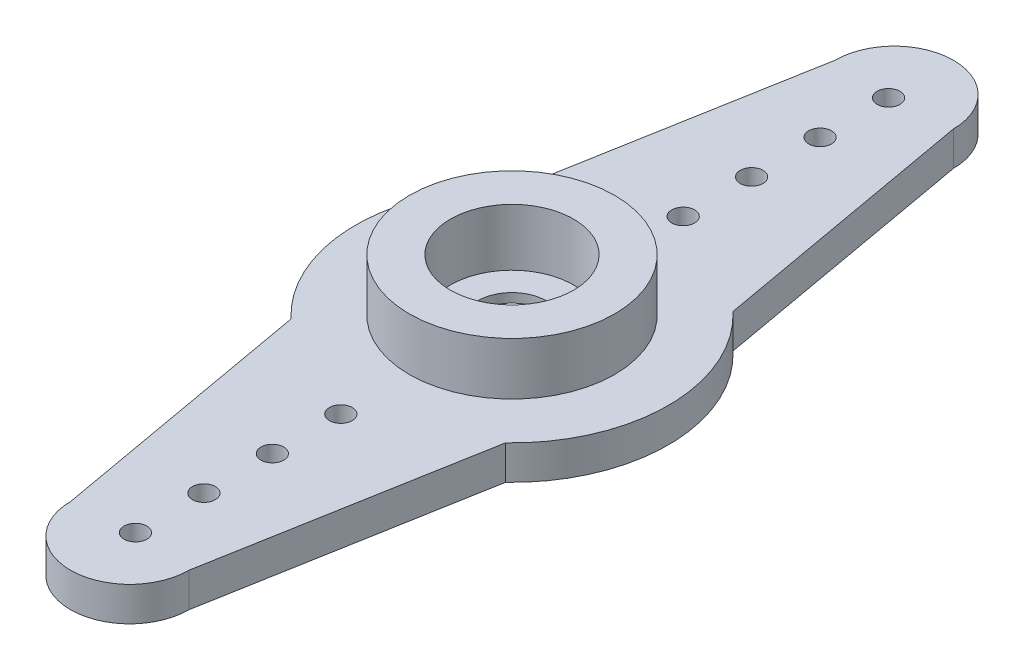
SolidWorks part; units mm, degrees
ref_plane "Alzado" through (0, 0, 0) normal (0, 0, 1) x (1, 0, 0)
ref_plane "Planta" through (0, 0, 0) normal (0, 1, 0) x (1, 0, 0)
ref_plane "Vista lateral" through (0, 0, 0) normal (1, 0, 0) x (0, 0, -1)
sketch "Croquis2" plane through (0, 0, 0) normal (0, 1, 0) x (1, 0, 0)
  line L0 (0, -19.35) -> (0, 19.35) construction
  line L1 (2.6, 16.75) -> (4.7, 4.9832)
  line L2 (-2.6, -16.75) -> (-4.7, -4.9832)
  line L3 (-2.6, 16.75) -> (-4.7, 4.9832)
  line L4 (-6.85, 0) -> (6.85, 0) construction
  line L5 (2.6, -16.75) -> (4.7, -4.9832)
  line L7 (-6.85, 0) -> (6.85, 0) construction
  arc A0 (-6.85, 0) -> (-4.7, -4.9832) centre (0, 0) ccw construction
  circle A1 centre (0, -16.5) radius 0.5
  circle A2 centre (0, -13.5) radius 0.5
  circle A3 centre (0, -10.5) radius 0.5
  arc A4 (2.6, 16.75) -> (-2.6, 16.75) centre (0, 16.75) ccw
  circle A5 centre (0, -7.5) radius 0.5
  circle A6 centre (0, 7.5) radius 0.5
  circle A7 centre (0, 10.5) radius 0.5
  circle A8 centre (0, 13.5) radius 0.5
  circle A9 centre (0, 16.5) radius 0.5
  arc A10 (2.6, -16.75) -> (-2.6, -16.75) centre (0, -16.75) cw
  arc A23 (4.7, -4.9832) -> (4.7, 4.9832) centre (0, 0) ccw construction
  arc A26 (-4.7, 4.9832) -> (-4.7, -4.9832) centre (0, 0) ccw
  arc A27 (4.7, -4.9832) -> (4.7, 4.9832) centre (0, 0) ccw
  circle A28 centre (0, 19.5) radius 0.5 [skipped]
  circle A29 centre (0, 22.5) radius 0.5 [skipped]
  circle A30 centre (0, 25.5) radius 0.5 [skipped]
  dimension "D7" = 5.2
  dimension "D8" = 1
  dimension "D2" = 19.35
  dimension "D4" = 9.4
  dimension "D9" = 7.5
  dimension "D11" = 3
  dimension "D12" = 13.7
  dimension "D10" = 7
extrude "Saliente-Extruir1" add sketch "Croquis2" along normal blind 1.5
sketch "Croquis3" plane through (0, 1.5, 0) normal (0, 1, 0) x (1, 0, 0)
  circle A0 centre (0, 0) radius 4.5
  dimension "D1" = 9
extrude "Saliente-Extruir2" add sketch "Croquis3" along normal blind 2.3
sketch "Croquis4" plane through (0, 0, 0) normal (0, -1, 0) x (1, 0, 0)
  circle A0 centre (0, 0) radius 3
  dimension "D1" = 6
extrude "Cortar-Extruir1" cut sketch "Croquis4" against normal blind 0.9
sketch "Croquis5" plane through (0, 0.9, 0) normal (0, -1, 0) x (1, 0, 0)
  circle A0 centre (0, 0) radius 1.5
  dimension "D1" = 3
extrude "Cortar-Extruir2" cut sketch "Croquis5" against normal through all
sketch "Croquis6" plane through (0, 3.8, 0) normal (0, 1, 0) x (1, 0, 0)
  circle A0 centre (0, 0) radius 2.7
  dimension "D1" = 5.4
extrude "Cortar-Extruir3" cut sketch "Croquis6" against normal blind 2.5
